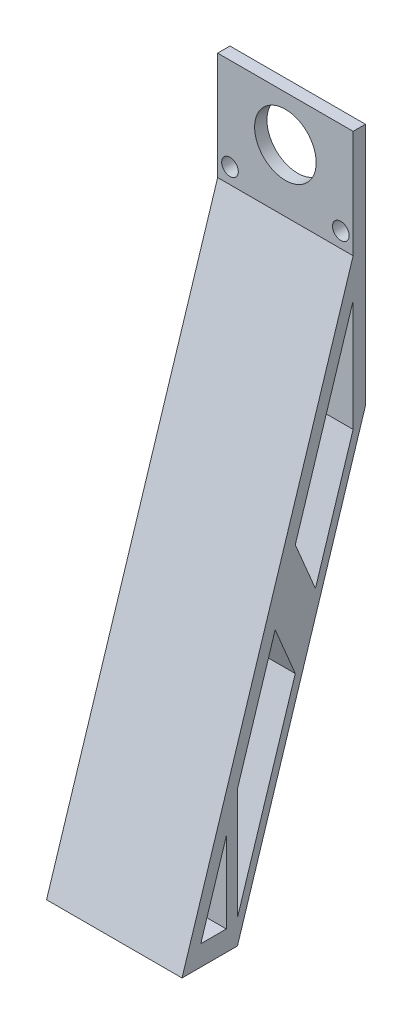
SolidWorks part; units mm, degrees
ref_plane "Front Plane" through (0, 0, 0) normal (0, 0, 1) x (1, 0, 0)
ref_plane "Top Plane" through (0, 0, 0) normal (0, 1, 0) x (1, 0, 0)
ref_plane "Right Plane" through (0, 0, 0) normal (1, 0, 0) x (0, 0, -1)
sketch "Sketch1" plane through (0, 0, 0) normal (0, 0, 1) x (1, 0, 0)
  line L1 (0, 0) -> (1117.6, 0)
  line L2 (0, 0) -> (0, 889)
  line L3 (0, 889) -> (1117.6, 889)
  line L4 (1117.6, 0) -> (1117.6, 889)
extrude "Boss-Extrude1" add sketch "Sketch1" along normal blind 101.6 contours L2 L3 L4 L1
sketch "Sketch6" plane through (0, 0, 101.6) normal (0, 0, 1) x (1, 0, 0)
  circle A0 centre (1016, 127) radius 68.58
  circle A1 centre (101.6, 127) radius 68.58
  circle A2 centre (558.8, 513.08) radius 254
extrude "Cut-Extrude1" cut sketch "Sketch6" against normal blind 492.76
sketch "Sketch12" plane through (0, 0, 0) normal (1, 0, 0) x (0, 0, -1)
  line L0 (0, 0) -> (-1411.4324, -4453.9281)
  line L2 (-1513.0324, -4453.9281) -> (-101.6, 0)
  line L3 (-1513.0324, -4453.9281) -> (-1411.4324, -4453.9281)
  line L5 (-101.6, 0) -> (0, 0)
extrude "Boss-Extrude4" add sketch "Sketch12" along normal blind 1117.6 contours L2 L5 L0 L3
sketch "Sketch18" plane through (0, 0, 0) normal (-1, 0, 0) x (0, 0, 1)
  line L0 (1411.4324, -4453.9281) -> (1055.8324, -4453.9281)
  line L1 (1055.8324, -4453.9281) -> (1055.8324, -4286.3753)
  line L2 (1055.8324, -4286.3753) -> (1358.3356, -4286.3753)
  line L3 (0, 0) -> (1411.4324, -4453.9281) construction
  line L4 (1358.3356, -4286.3753) -> (1411.4324, -4453.9281)
extrude "Boss-Extrude6" add sketch "Sketch18" against normal blind 1117.6
sketch "Sketch19" plane through (0, 0, 0) normal (-1, 0, 0) x (0, 0, 1)
  line L0 (1055.8324, -4286.3753) -> (1055.8324, -3331.7938)
  line L1 (0, 0) -> (1358.3356, -4286.3753) construction
  line L2 (1055.8324, -4286.3753) -> (1145.6519, -4286.3753)
  line L3 (1358.3356, -4286.3753) -> (1055.8324, -4286.3753) construction
  line L4 (1145.6519, -4286.3753) -> (1147.6003, -4288.3581)
  line L5 (1147.6003, -4288.3581) -> (1147.6003, -3621.3771)
  line L6 (1147.6003, -3621.3771) -> (1055.8324, -3331.7938)
extrude "Boss-Extrude7" add sketch "Sketch19" against normal blind 1117.6
sketch "Sketch21" plane through (0, 0, 0) normal (-1, 0, 0) x (0, 0, 1)
  line L0 (0, 0) -> (0, -1181.033)
sketch "Sketch22" plane through (0, 0, 0) normal (-1, 0, 0) x (0, 0, 1)
  line L0 (1055.8324, -4453.9281) -> (0, -1122.1344)
  line L1 (0, 0) -> (1055.8324, -3331.7938) construction
  line L2 (0, 0) -> (0, -1181.033) construction
  line L3 (101.6, -1442.7442) -> (101.6, -320.6098)
  line L4 (101.6, -1442.7442) -> (0, -1122.1344)
  line L5 (0, -1122.1344) -> (0, 0)
  line L6 (0, 0) -> (101.6, -320.6098)
  line L7 (101.6, 0) -> (101.6, 889) construction
sketch "Sketch24" plane through (0, 0, 0) normal (-1, 0, 0) x (0, 0, 1)
  line L0 (101.6, -1442.7442) -> (101.6, -320.6098) construction
  line L1 (101.6, -1240.5677) -> (1055.8324, -4251.7516)
  line L2 (1055.8324, -3331.7938) -> (1055.8324, -4453.9281) construction
  line L3 (1055.8324, -4453.9281) -> (0, -1122.1344) construction
  line L4 (101.6, -1240.5677) -> (101.6, -1442.7442)
  line L5 (101.6, -1442.7442) -> (1055.8324, -4453.9281)
  line L6 (1055.8324, -4453.9281) -> (1055.8324, -4251.7516)
extrude "Boss-Extrude8" add sketch "Sketch24" against normal blind 1117.6
extrude "Boss-Extrude9" add sketch "Sketch22" against normal blind 1117.6 contours L4 L3 L6 L5
sketch "Sketch27" plane through (0, 0, 0) normal (-1, 0, 0) x (0, 0, 1)
  line L0 (578.7162, -2746.1597) -> (744.7859, -2350.2527)
  line L1 (1055.8324, -4251.7516) -> (101.6, -1240.5677) construction
  line L2 (101.6, -320.6098) -> (1055.8324, -3331.7938) construction
  line L3 (744.7859, -2350.2527) -> (578.7162, -1826.2018)
  line L4 (578.7162, -1826.2018) -> (412.6465, -2222.1087)
  line L5 (412.6465, -2222.1087) -> (578.7162, -2746.1597)
extrude "Boss-Extrude10" add sketch "Sketch27" against normal blind 1117.6
